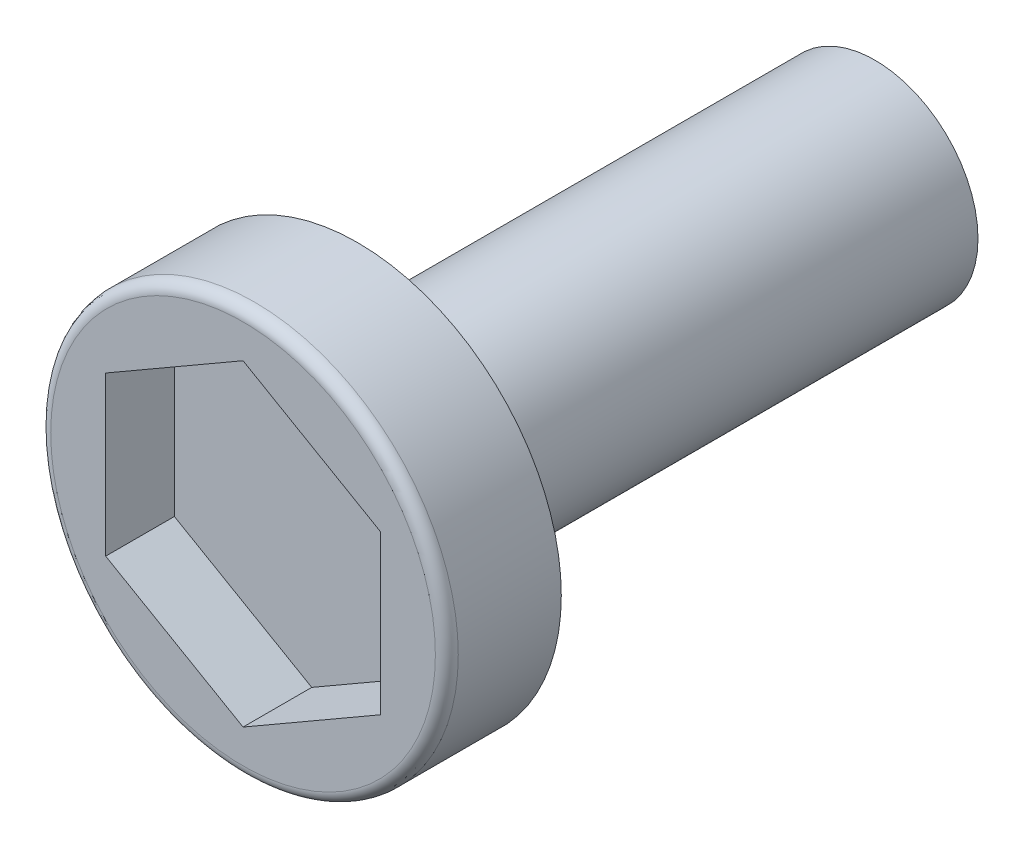
SolidWorks part; units mm, degrees
ref_plane "Alzado" through (0, 0, 0) normal (0, 0, 1) x (1, 0, 0)
ref_plane "Planta" through (0, 0, 0) normal (0, 1, 0) x (1, 0, 0)
ref_plane "Vista lateral" through (0, 0, 0) normal (1, 0, 0) x (0, 0, -1)
sketch "Croquis1" plane through (0, 0, 0) normal (0, 0, 1) x (1, 0, 0)
  circle A0 centre (0, 0) radius 8.9
  dimension "D1" = 17.8
extrude "Saliente-Extruir1" add sketch "Croquis1" along normal blind 5
sketch "Croquis2" plane through (0, 0, 5) normal (0, 0, 1) x (1, 0, 0)
  line L1 (-6, -3.4641) -> (0, -6.9282)
  line L2 (0, -6.9282) -> (6, -3.4641)
  line L3 (6, -3.4641) -> (6, 3.4641)
  line L4 (6, 3.4641) -> (0, 6.9282)
  line L5 (0, 6.9282) -> (-6, 3.4641)
  line L6 (-6, 3.4641) -> (-6, -3.4641)
  circle A0 centre (0, 0) radius 6 construction
  dimension "D1" = 12
extrude "Cortar-Extruir1" cut sketch "Croquis2" against normal blind 3
fillet "Redondeo1" radius 0.5 1 edges at (8.9, 0, 5)
sketch "Croquis3" plane through (0, 0, 0) normal (0, 0, -1) x (-1, 0, 0)
  circle A0 centre (0, 0) radius 4.5
  dimension "D1" = 9
extrude "Saliente-Extruir2" add sketch "Croquis3" along normal blind 22.6
